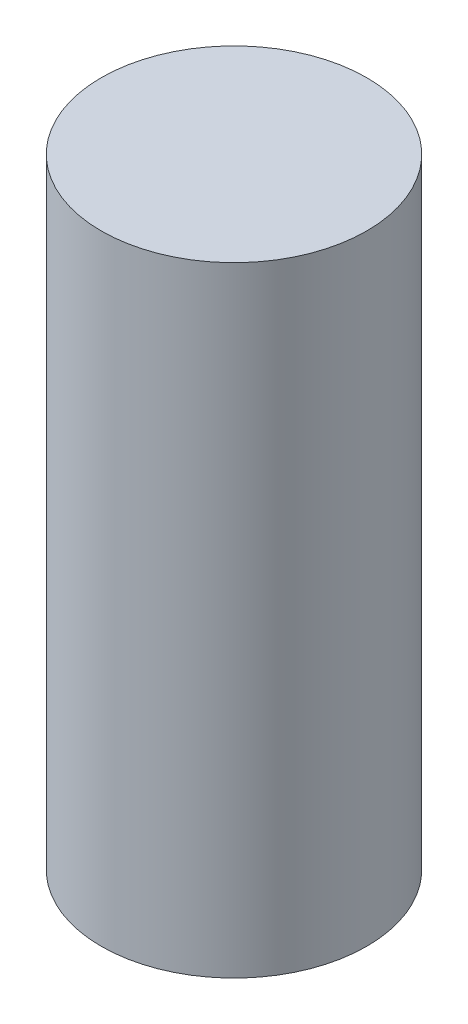
SolidWorks part; units mm, degrees
ref_plane "前视基准面" through (0, 0, 0) normal (0, 0, 1) x (1, 0, 0)
ref_plane "上视基准面" through (0, 0, 0) normal (0, 1, 0) x (1, 0, 0)
ref_plane "右视基准面" through (0, 0, 0) normal (1, 0, 0) x (0, 0, -1)
other "Configuration Table"
sketch "草图1" plane through (0, 0, 0) normal (0, 1, 0) x (1, 0, 0)
  circle A0 centre (0, 0) radius 1.5
  dimension "D1" = 3
extrude "凸台-拉伸1" add sketch "草图1" along normal blind 7
